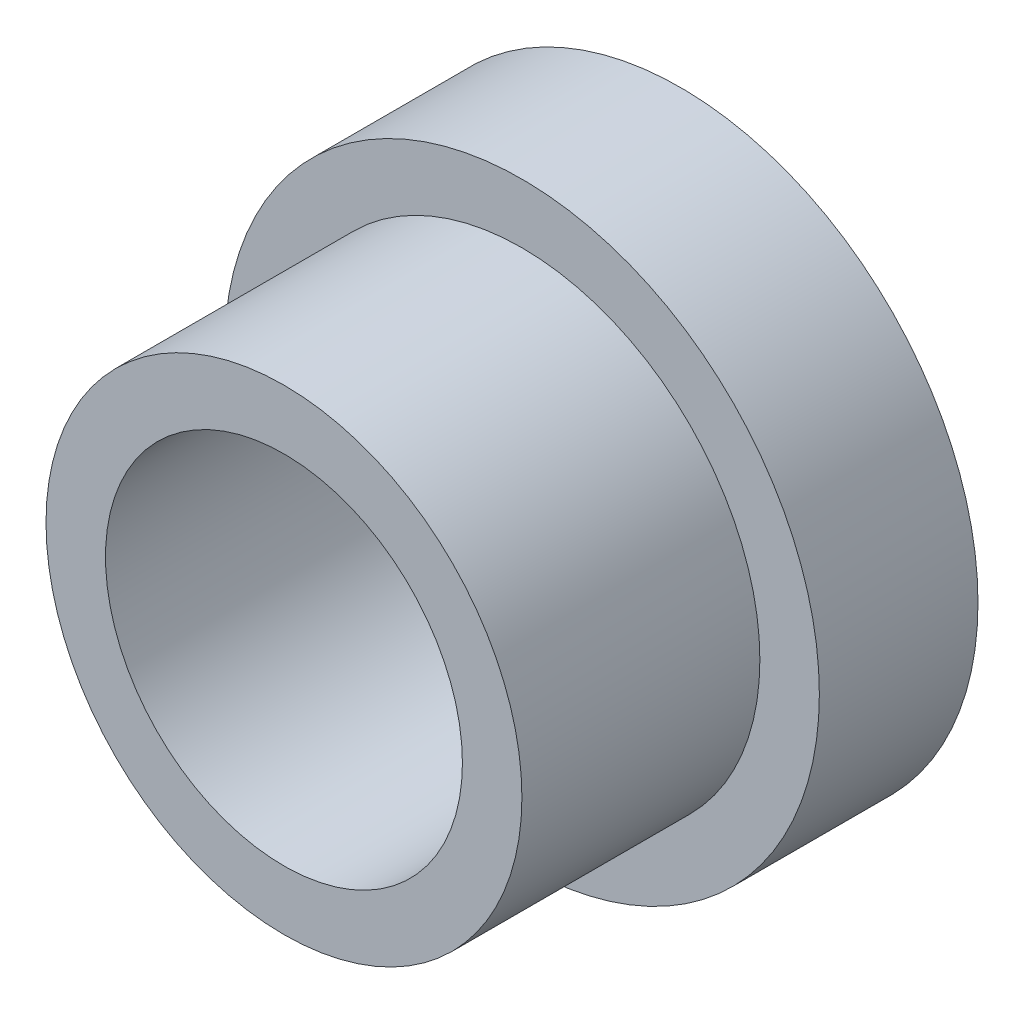
SolidWorks part; units mm, degrees
ref_plane "Plan de face" through (0, 0, 0) normal (0, 0, 1) x (1, 0, 0)
ref_plane "Plan de dessus" through (0, 0, 0) normal (0, 1, 0) x (1, 0, 0)
ref_plane "Plan de droite" through (0, 0, 0) normal (1, 0, 0) x (0, 0, -1)
sketch "Esquisse1" plane through (0, 0, 0) normal (0, 0, 1) x (1, 0, 0)
  circle A0 centre (0, 0) radius 7.5
  dimension "D1" = 15
extrude "Boss.-Extru.1" add sketch "Esquisse1" along normal blind 4
sketch "Esquisse2" plane through (0, 0, 4) normal (0, 0, 1) x (1, 0, 0)
  circle A0 centre (0, 0) radius 6
  dimension "D1" = 12
extrude "Boss.-Extru.2" add sketch "Esquisse2" along normal blind 6
sketch "Esquisse3" plane through (0, 0, 10) normal (0, 0, 1) x (1, 0, 0)
  circle A0 centre (0, 0) radius 4.5
  dimension "D1" = 9
extrude "Enlèv. mat.-Extru.1" cut sketch "Esquisse3" against normal through all
